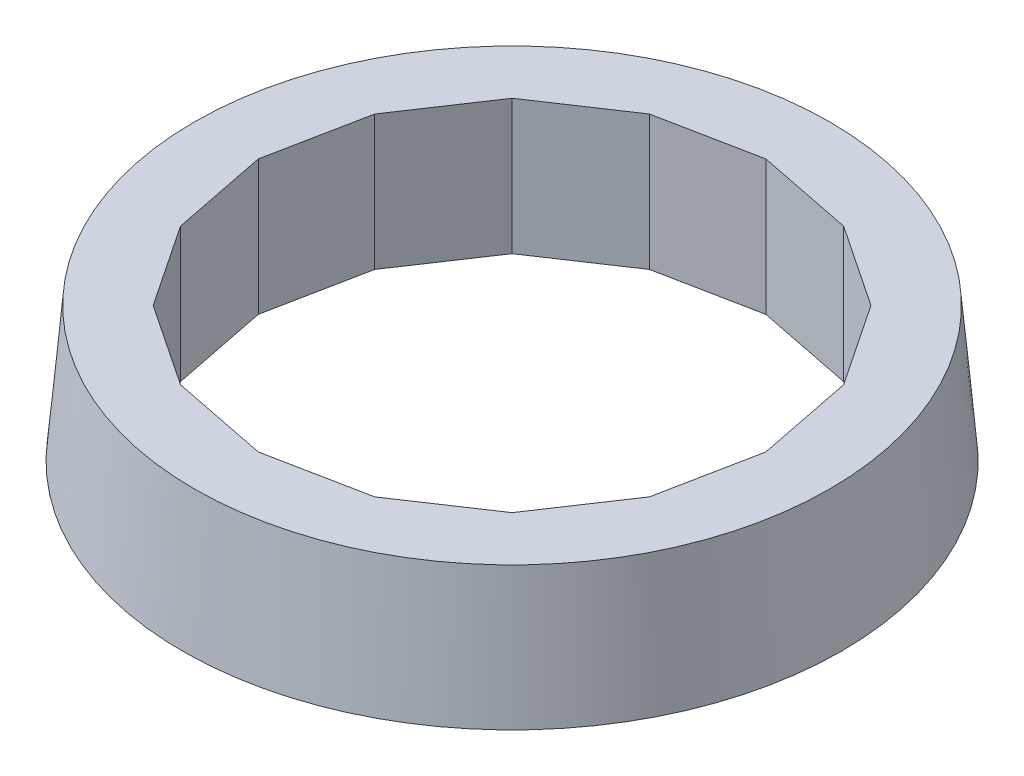
SolidWorks part; units mm, degrees
ref_plane "Front Plane" through (0, 0, 0) normal (0, 0, 1) x (1, 0, 0)
ref_plane "Top Plane" through (0, 0, 0) normal (0, 1, 0) x (1, 0, 0)
ref_plane "Right Plane" through (0, 0, 0) normal (1, 0, 0) x (0, 0, -1)
sketch "Sketch1" plane through (0, 0, 0) normal (0, 1, 0) x (1, 0, 0)
  line L0 (-55.3333, 0) -> (0, 0) construction
  line L1 (-55.3333, 0) -> (-51.1213, -21.1752)
  line L2 (-51.1213, -21.1752) -> (-39.1266, -39.1266)
  line L3 (-39.1266, -39.1266) -> (-21.1752, -51.1213)
  line L4 (-21.1752, -51.1213) -> (0, -55.3333)
  line L5 (0, -55.3333) -> (21.1752, -51.1213)
  line L6 (21.1752, -51.1213) -> (39.1266, -39.1266)
  line L7 (39.1266, -39.1266) -> (51.1213, -21.1752)
  line L8 (51.1213, -21.1752) -> (55.3333, 0)
  line L9 (55.3333, 0) -> (51.1213, 21.1752)
  line L10 (51.1213, 21.1752) -> (39.1266, 39.1266)
  line L11 (39.1266, 39.1266) -> (21.1752, 51.1213)
  line L12 (21.1752, 51.1213) -> (0, 55.3333)
  line L13 (0, 55.3333) -> (-21.1752, 51.1213)
  line L14 (-21.1752, 51.1213) -> (-39.1266, 39.1266)
  line L15 (-39.1266, 39.1266) -> (-51.1213, 21.1752)
  line L16 (-51.1213, 21.1752) -> (-55.3333, 0)
  line L18 (-35.9101, 0) -> (-33.1766, -13.7422)
  line L19 (-33.1766, -13.7422) -> (-25.3923, -25.3923)
  line L20 (-25.3923, -25.3923) -> (-13.7422, -33.1766)
  line L21 (-13.7422, -33.1766) -> (0, -35.9101)
  line L22 (0, -35.9101) -> (13.7422, -33.1766)
  line L23 (13.7422, -33.1766) -> (25.3923, -25.3923)
  line L24 (25.3923, -25.3923) -> (33.1766, -13.7422)
  line L25 (33.1766, -13.7422) -> (35.9101, 0)
  line L26 (35.9101, 0) -> (33.1766, 13.7422)
  line L27 (33.1766, 13.7422) -> (25.3923, 25.3923)
  line L28 (25.3923, 25.3923) -> (13.7422, 33.1766)
  line L29 (13.7422, 33.1766) -> (0, 35.9101)
  line L30 (0, 35.9101) -> (-13.7422, 33.1766)
  line L31 (-13.7422, 33.1766) -> (-25.3923, 25.3923)
  line L32 (-25.3923, 25.3923) -> (-33.1766, 13.7422)
  line L33 (-33.1766, 13.7422) -> (-35.9101, 0)
  circle A0 centre (0, 0) radius 54.2701 construction
  circle A1 centre (0, 0) radius 35.2201 construction
  dimension "D1" = 21.59
  dimension "D2" = 19.05
extrude "Boss-Extrude1" add sketch "Sketch1" along normal blind 19.05
sketch "Sketch3" plane through (0, 0, 0) normal (0, 0, 1) x (1, 0, 0)
  line L0 (-46.6368, 0) -> (-44.45, 24.9947)
  line L2 (-44.45, 24.9947) -> (-114.9632, 24.9947)
  line L3 (-114.9632, 24.9947) -> (-114.9632, 0)
  line L4 (-114.9632, 0) -> (-46.6368, 0)
  line L5 (0, 0) -> (0, 19.05) construction
  dimension "D1" = 95
  dimension "D2" = 44.45
revolve "Cut-Revolve1" cut sketch "Sketch3" angle 360 about L5
